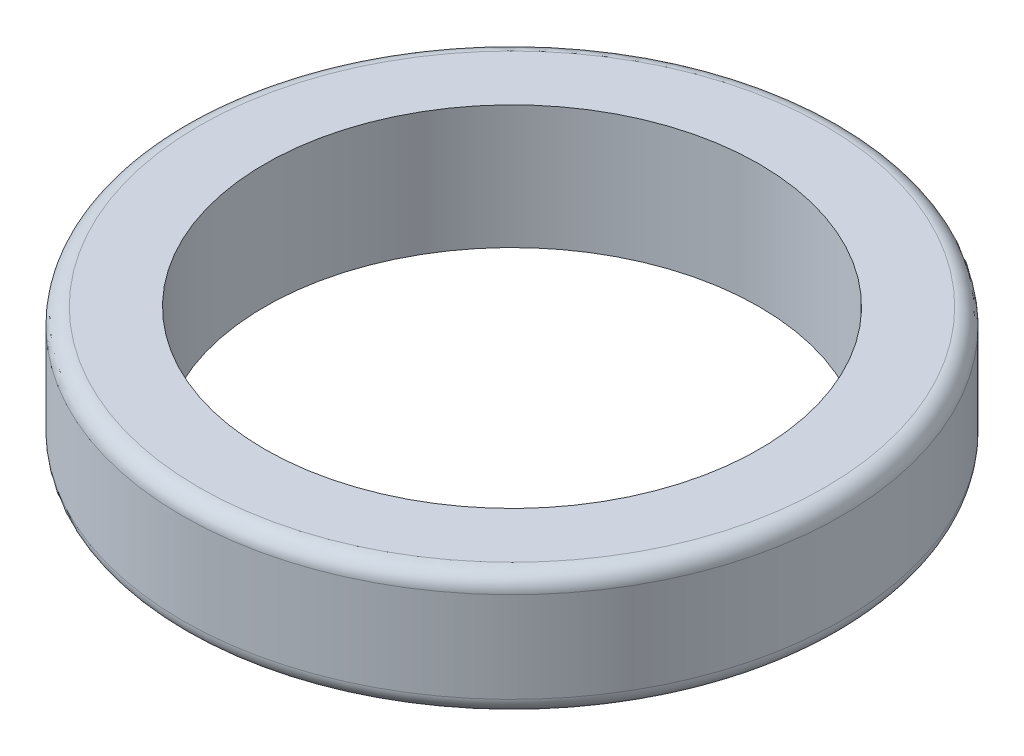
SolidWorks part; units mm, degrees
ref_plane "Ebene vorne" through (0, 0, 0) normal (0, 0, 1) x (1, 0, 0)
ref_plane "Ebene oben" through (0, 0, 0) normal (0, 1, 0) x (1, 0, 0)
ref_plane "Ebene rechts" through (0, 0, 0) normal (1, 0, 0) x (0, 0, -1)
sketch "Skizze1" plane through (0, 0, 0) normal (0, 1, 0) x (1, 0, 0)
  circle A0 centre (0, 0) radius 3
  circle A1 centre (0, 0) radius 4
  dimension "D1" = 6
  dimension "D2" = 1
extrude "Aufsatz-Linear austragen1" add sketch "Skizze1" along normal blind 1.5
fillet "Verrundung1" radius 0.2 2 edges at (0, 0, 4) (0, 1.5, 4)
